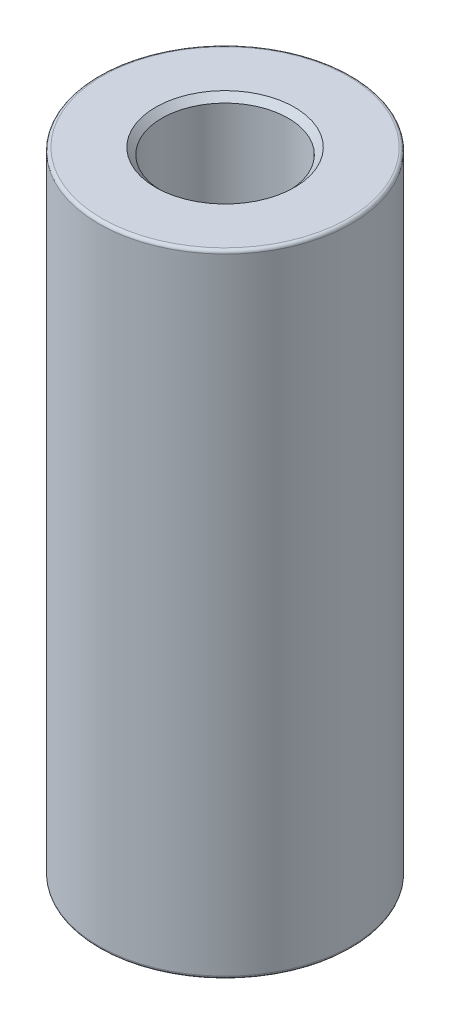
SolidWorks part; units mm, degrees
ref_plane "Спереди" through (0, 0, 0) normal (0, 0, 1) x (1, 0, 0)
ref_plane "Сверху" through (0, 0, 0) normal (0, 1, 0) x (1, 0, 0)
ref_plane "Справа" through (0, 0, 0) normal (1, 0, 0) x (0, 0, -1)
sketch "Эскиз1" plane through (0, 0, 0) normal (0, 1, 0) x (1, 0, 0)
  circle A0 centre (0, 0) radius 40
extrude "Бобышка-Вытянуть1" add sketch "Эскиз1" along normal blind 200
sketch "Эскиз2" plane through (0, 200, 0) normal (0, 1, 0) x (1, 0, 0)
  circle A0 centre (0, 0) radius 20
extrude "Вырез-Вытянуть1" cut sketch "Эскиз2" against normal blind 150
chamfer "Фаска1" distance 2 angle 45 1 edges at (0, 200, 20)
fillet "Скругление1" radius 1 1 edges at (0, 0, 40)
fillet "Скругление2" radius 1 1 edges at (0, 200, 40)
